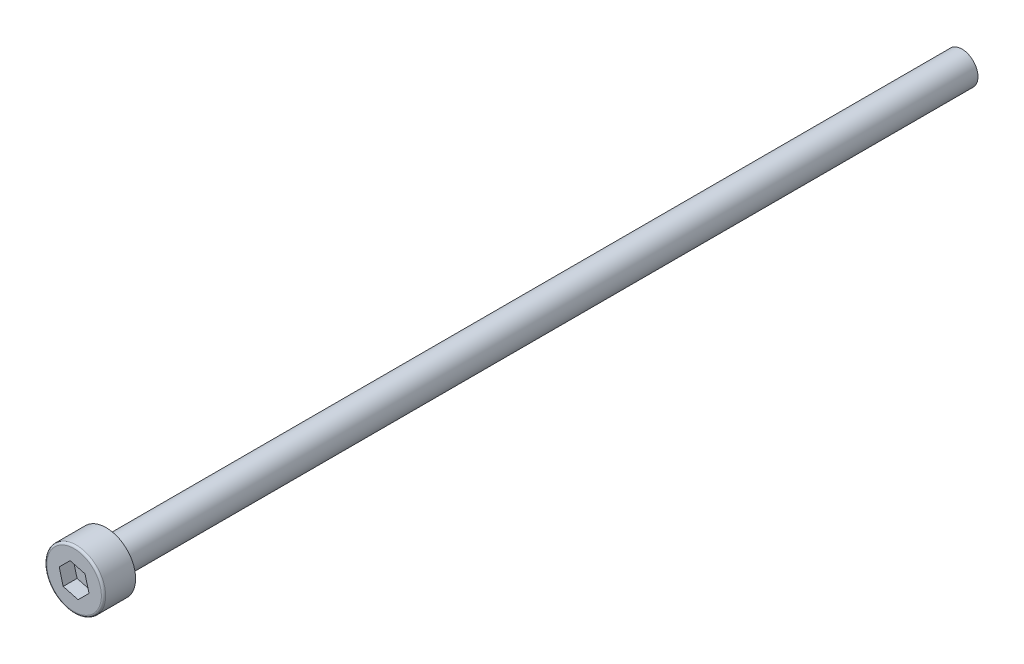
SolidWorks part; units mm, degrees
ref_plane "前视基准面" through (0, 0, 0) normal (0, 0, 1) x (1, 0, 0)
ref_plane "上视基准面" through (0, 0, 0) normal (0, 1, 0) x (1, 0, 0)
ref_plane "右视基准面" through (0, 0, 0) normal (1, 0, 0) x (0, 0, -1)
sketch "草图1" plane through (0, 0, 0) normal (0, 0, 1) x (1, 0, 0)
  circle A0 centre (0, 0) radius 2.75
  dimension "D1" = 5.5
extrude "凸台-拉伸1" add sketch "草图1" along normal blind 3
sketch "草图2" plane through (0, 0, 3) normal (0, 0, 1) x (1, 0, 0)
  line L1 (-1.0206, -1.0206) -> (0.3736, -1.3942)
  line L2 (0.3736, -1.3942) -> (1.3942, -0.3736)
  line L3 (1.3942, -0.3736) -> (1.0206, 1.0206)
  line L4 (1.0206, 1.0206) -> (-0.3736, 1.3942)
  line L5 (-0.3736, 1.3942) -> (-1.3942, 0.3736)
  line L6 (-1.3942, 0.3736) -> (-1.0206, -1.0206)
  circle A0 centre (0, 0) radius 1.25 construction
  dimension "D1" = 2.5
extrude "切除-拉伸1" cut sketch "草图2" against normal blind 1.3
sketch "草图3" plane through (0, 0, 0) normal (0, 0, -1) x (-1, 0, 0)
  circle A0 centre (0, 0) radius 1.5
  dimension "D1" = 3
extrude "凸台-拉伸2" add sketch "草图3" along normal blind 80
fillet "圆角1" radius 0.2 1 edges at (2.75, 0, 3)
